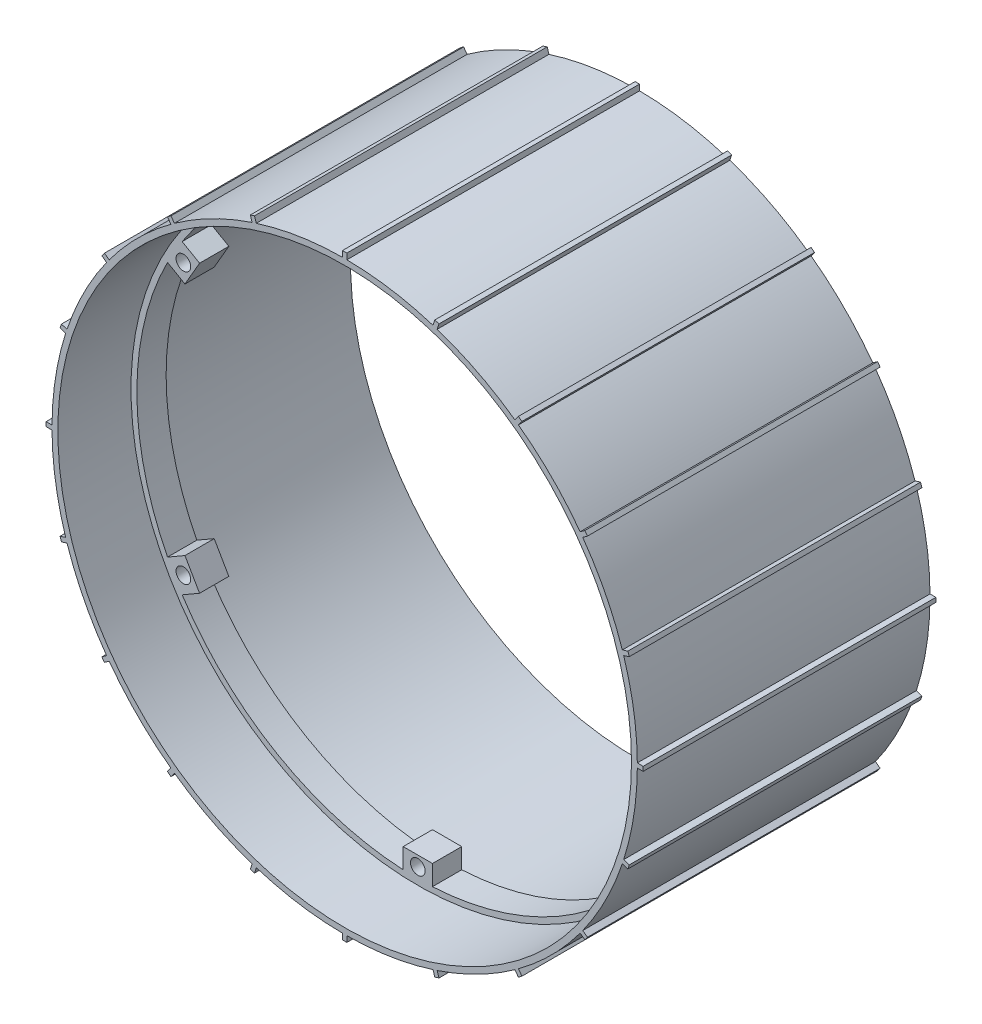
SolidWorks part; units mm, degrees
material "POLYURETHANE (11671)"
ref_plane "Front Plane" through (0, 0, 0) normal (0, 0, 1) x (1, 0, 0)
ref_plane "Top Plane" through (0, 0, 0) normal (0, 1, 0) x (1, 0, 0)
ref_plane "Right Plane" through (0, 0, 0) normal (1, 0, 0) x (0, 0, -1)
sketch "Sketch2" plane through (0, 0, 0) normal (0, 0, 1) x (1, 0, 0)
  circle A0 centre (0, 0) radius 100
  circle A2 centre (0, 0) radius 98
  dimension "D1" = 200
  dimension "D2" = 2
extrude "Boss-Extrude2" add sketch "Sketch2" along normal mid plane 100
sketch "Sketch4" plane through (0, 0, 0) normal (0, 0, 1) x (1, 0, 0)
  line L0 (0, 0) -> (0, 127.3155) construction
  line L1 (0, 101.9972) -> (-0.75, 101.9972)
  line L2 (-0.75, 101.9972) -> (-0.75, 99.9972)
  line L3 (0, 101.9972) -> (0.75, 101.9972)
  line L4 (0.75, 101.9972) -> (0.75, 99.9972)
  line L5 (-0.75, 99.9972) -> (0.75, 99.9972)
  circle A2 centre (0, 0) radius 100 construction
  dimension "D1" = 1.5
  dimension "D2" = 0.75
  dimension "D3" = 2
extrude "Boss-Extrude3" add sketch "Sketch4" along normal mid plane 100
pattern_circular "CirPattern1" count 20 over 360 about axis through (0, 0, 0) along (0, 0, 1) of "Boss-Extrude3"
ref_plane "Plane2" through (0, 0, 20) normal (0, 0, 1) x (1, 0, 0)
sketch "Sketch7" plane through (0, 0, 20) normal (0, 0, 1) x (1, 0, 0)
  circle A0 centre (0, 0) radius 98
  circle A1 centre (0, 0) radius 96
  dimension "D1" = 2
extrude "Boss-Extrude5" add sketch "Sketch7" along normal mid plane 10
sketch "Sketch14" plane through (0, 0, 25) normal (0, 0, 1) x (1, 0, 0)
  line L0 (0, 0) -> (0, 107.0915) construction
  line L1 (-5, 96) -> (5, 96)
  line L2 (5, 96) -> (5, 89)
  line L5 (5, 89) -> (-5, 89)
  line L6 (-5, 89) -> (-5, 96)
  circle A0 centre (0, 0) radius 98 construction
  dimension "D1" = 10
  dimension "D2" = 5
  dimension "D3" = 7
  dimension "D4" = 96
extrude "Boss-Extrude8" add sketch "Sketch14" against normal blind 10
sketch "Sketch15" plane through (0, 0, 25) normal (0, 0, 1) x (1, 0, 0)
  line L0 (-5, 95.8697) -> (-5, 89) construction
  line L1 (-5, 89) -> (5, 89) construction
  circle A0 centre (0, 92.5) radius 2.5
  dimension "D1" = 5
  dimension "D2" = 5
  dimension "D3" = 3.5
extrude "Cut-Extrude3" cut sketch "Sketch15" against normal blind 10
pattern_circular "CirPattern6" count 6 over 360 about axis through (0, 0, 0) along (0, 0, 1) of "Boss-Extrude8", "Cut-Extrude3"
